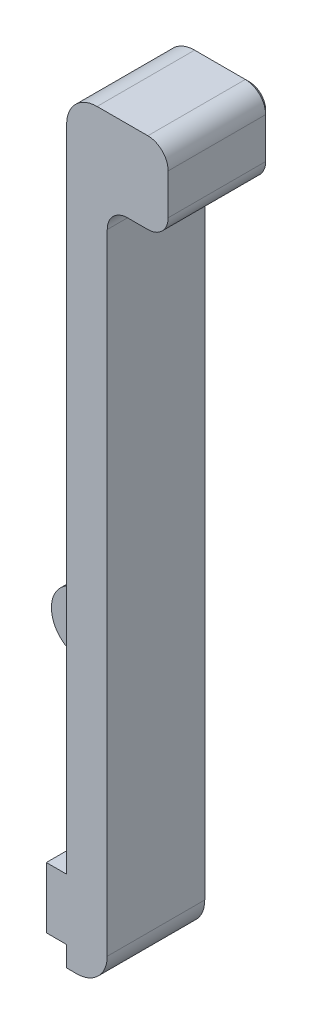
SolidWorks part; units mm, degrees
ref_plane "Front Plane" through (0, 0, 0) normal (0, 0, 1) x (1, 0, 0)
ref_plane "Top Plane" through (0, 0, 0) normal (0, 1, 0) x (1, 0, 0)
ref_plane "Right Plane" through (0, 0, 0) normal (1, 0, 0) x (0, 0, -1)
sketch "Sketch1" plane through (0, 0, 0) normal (0, 0, 1) x (1, 0, 0)
  line L0 (2.54, 47.625) -> (7.62, 47.625)
  line L1 (1.27, 47.625) -> (2.54, 47.625)
  line L2 (-2.54, 43.815) -> (-2.54, -10.795)
  line L3 (-2.54, -47.625) -> (-1.27, -47.625)
  line L4 (2.54, 34.925) -> (2.54, -43.815)
  line L5 (-2.54, 47.625) -> (2.54, -47.625) construction
  line L6 (-2.54, -47.625) -> (2.54, 47.625) construction
  line L7 (10.16, 45.085) -> (10.16, 40.005)
  line L8 (7.62, 37.465) -> (5.08, 37.465)
  line L9 (-2.54, -45.085) -> (-5.08, -45.085)
  line L10 (-5.08, -45.085) -> (-5.08, -37.465)
  line L11 (-5.08, -37.465) -> (-2.54, -37.465)
  line L12 (-3.81, -12.065) -> (-6.985, -12.065)
  line L13 (-2.54, -15.875) -> (-6.985, -15.875) construction
  line L14 (-3.81, -19.685) -> (-6.985, -19.685)
  line L15 (-2.54, -20.955) -> (-2.54, -37.465)
  line L16 (-2.54, -45.085) -> (-2.54, -47.625)
  arc A0 (-6.985, -12.065) -> (-6.985, -19.685) centre (-6.985, -15.875) ccw
  circle A1 centre (-6.985, -15.875) radius 1.7
  arc A2 (-2.54, -20.955) -> (-3.81, -19.685) centre (-3.81, -20.955) ccw
  arc A3 (-2.54, -10.795) -> (-3.81, -12.065) centre (-3.81, -10.795) cw
  arc A4 (7.62, 47.625) -> (10.16, 45.085) centre (7.62, 45.085) cw
  arc A5 (10.16, 40.005) -> (7.62, 37.465) centre (7.62, 40.005) cw
  arc A6 (2.54, 34.925) -> (5.08, 37.465) centre (5.08, 34.925) cw
  arc A7 (-2.54, 43.815) -> (1.27, 47.625) centre (1.27, 43.815) cw
  arc A8 (-1.27, -47.625) -> (2.54, -43.815) centre (-1.27, -43.815) ccw
  point P0 (0, 0)
  point P24 (-2.54, -19.685)
  point P27 (-2.54, -12.065)
  point P32 (10.16, 47.625)
  point P35 (10.16, 37.465)
  point P38 (2.54, 37.465)
  dimension "D3" = 3.4
  dimension "D7" = 1.27
  dimension "D13" = 2.54
  dimension "D14" = 3.81
  dimension "D15" = 3.81
  dimension "D1" = 2.54
  dimension "D2" = 7.62
  dimension "D4" = 7.62
  dimension "D5" = 5.08
  dimension "D6" = 4.445
  dimension "D8" = 95.25
  dimension "D9" = 7.62
  dimension "D10" = 2.54
  dimension "D11" = 10.16
  dimension "D12" = 31.75
extrude "Boss-Extrude1" add sketch "Sketch1" along normal blind 12.7
sketch "Sketch2" plane through (-2.54, 0, 0) normal (-1, 0, 0) x (0, 0, 1)
  line L0 (12.7, -10.795) -> (0, -10.795) construction
  line L1 (6.35, -10.795) -> (12.7, -10.795)
  line L2 (6.35, -10.795) -> (6.35, -20.955)
  line L3 (6.35, -20.955) -> (12.7, -20.955)
  line L4 (12.7, -10.795) -> (12.7, -20.955)
  line L5 (12.7, -20.955) -> (0, -20.955) construction
  dimension "D1" = 6.35
extrude "Cut-Extrude1" cut sketch "Sketch2" along normal blind 20.32
sketch "Sketch3" plane through (-2.54, 0, 0) normal (-1, 0, 0) x (0, 0, 1)
  line L0 (12.7, -37.465) -> (0, -37.465) construction
  line L1 (6.35, 43.815) -> (6.35, -19.685) construction
  line L2 (12.7, 43.815) -> (0, 43.815) construction
  circle A0 centre (6.35, -19.685) radius 1.7
  dimension "D2" = 3.4
  dimension "D1" = 17.78
chamfer "Chamfer1" distance 0.5 angle 45 22 edges at (-5.285, -15.875, 0) (-1.905, -47.625, 0) (1.4241, -46.5091, 0) (2.54, -4.445, 0) (3.2839, 36.7211, 0) (6.35, 37.465, 0) (9.4161, 38.2089, 0) (10.16, 42.545, 0) (9.4161, 46.8811, 0) (4.445, 47.625, 0) (-1.4241, 46.5091, 0) (-2.54, 16.51, 0) (-2.912, -11.693, 0) (-5.3975, -12.065, 0) (-10.795, -15.875, 0) (-5.3975, -19.685, 0) (-2.912, -20.057, 0) (-2.54, -29.21, 0) (-3.81, -37.465, 0) (-5.08, -41.275, 0) (-3.81, -45.085, 0) (-2.54, -46.355, 0)
